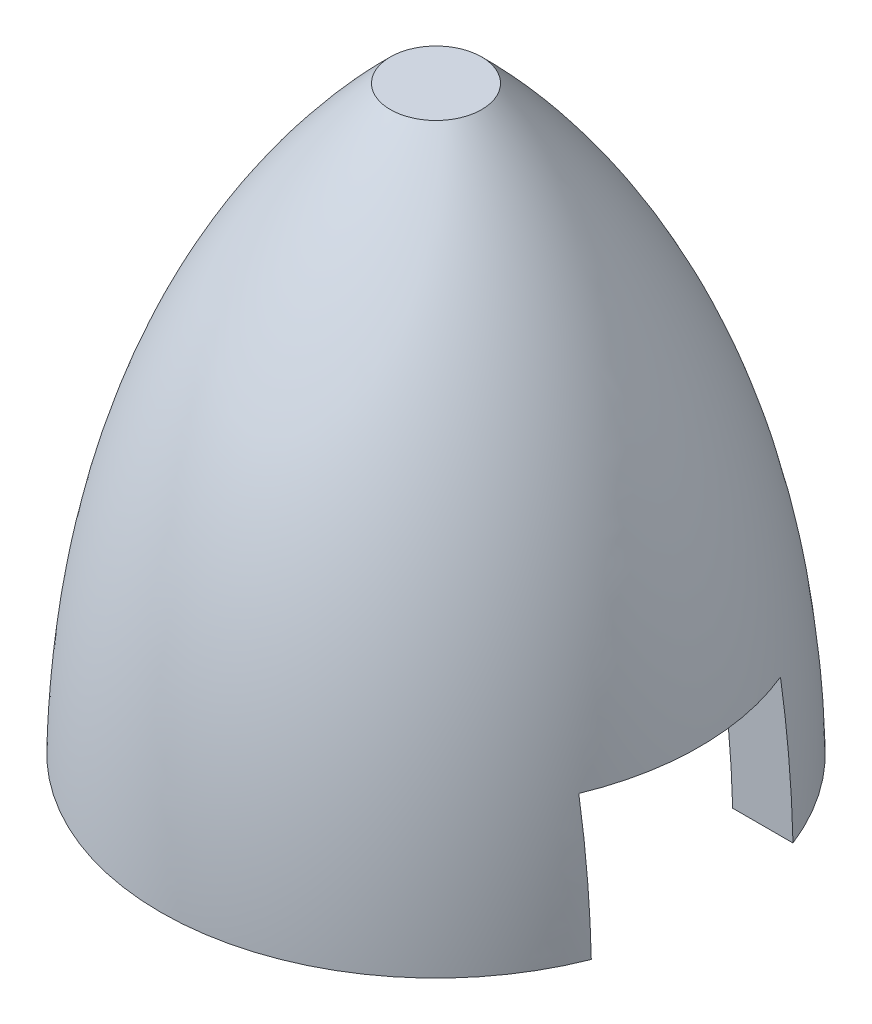
SolidWorks part; units mm, degrees
material "Spinner"
ref_plane "Front Plane" through (0, 0, 0) normal (0, 0, 1) x (1, 0, 0)
ref_plane "Top Plane" through (0, 0, 0) normal (0, 1, 0) x (1, 0, 0)
ref_plane "Right Plane" through (0, 0, 0) normal (1, 0, 0) x (0, 0, -1)
sketch "Sketch1" plane through (0, 0, 0) normal (0, 1, 0) x (1, 0, 0)
  circle A0 centre (0, 0) radius 15
  dimension "D1" = 30
sketch "Sketch2" plane through (0, 0, 0) normal (1, 0, 0) x (0, 0, -1)
  line L0 (0, 0) -> (0, 31.65)
  point P3 (0, 0)
  dimension "D1" = 31.65
ref_plane "Plane1" through (0, 31.65, 0) normal (0, 1, 0) x (1, 0, 0)
sketch "Sketch4" plane through (0, 31.65, 0) normal (0, 1, 0) x (1, 0, 0)
  circle A0 centre (0, 0) radius 2.5
sketch "Sketch5" plane through (0, 0, 0) normal (1, 0, 0) x (0, 0, -1)
  line L0 (0, 31.65) -> (2.49, 31.65)
  line L1 (15.0131, 0) -> (0, 0)
  line L2 (0, 0) -> (0, 31.65)
  line L3 (0, 28.65) -> (1.2324, 28.65)
  spline S0 degree 2 poles (15.0131, 0) (14.5549, 19.7503) (2.49, 31.65) knots 0 0 0 0.95204 0.95204 0.95204
  spline S1 degree 1 poles (12.0139, -0.0696) (1.2324, 28.65) knots 0 0 1 1 construction
  spline S2 degree 2 poles (1.2324, 28.65) (5.1046, 24.5827) (9.2365, 16.2274) (11.8493, 6.7239) (12.0139, -0.0696) knots 0 0 0 0.343216 0.572027 0.915244 0.915244 0.915244
revolve "Revolve1" add sketch "Sketch5" angle 360 about L2
sketch "Sketch7" plane through (0, 0, 0) normal (1, 0, 0) x (0, 0, -1)
  line L0 (-5.5, -7.5) -> (5.5, -7.5)
  line L1 (-5.5, -7.5) -> (-5.5, 7.5)
  line L2 (5.5, -7.5) -> (5.5, 7.5)
  line L3 (-5.5, 7.5) -> (5.5, 7.5)
  line L4 (-5.5, -7.5) -> (5.5, 7.5) construction
  line L5 (5.5, -7.5) -> (-5.5, 7.5) construction
  point P1 (0, 0)
  dimension "D1" = 11
  dimension "D2" = 15
extrude "Cut-Extrude1" cut sketch "Sketch7" against normal mid plane 50
